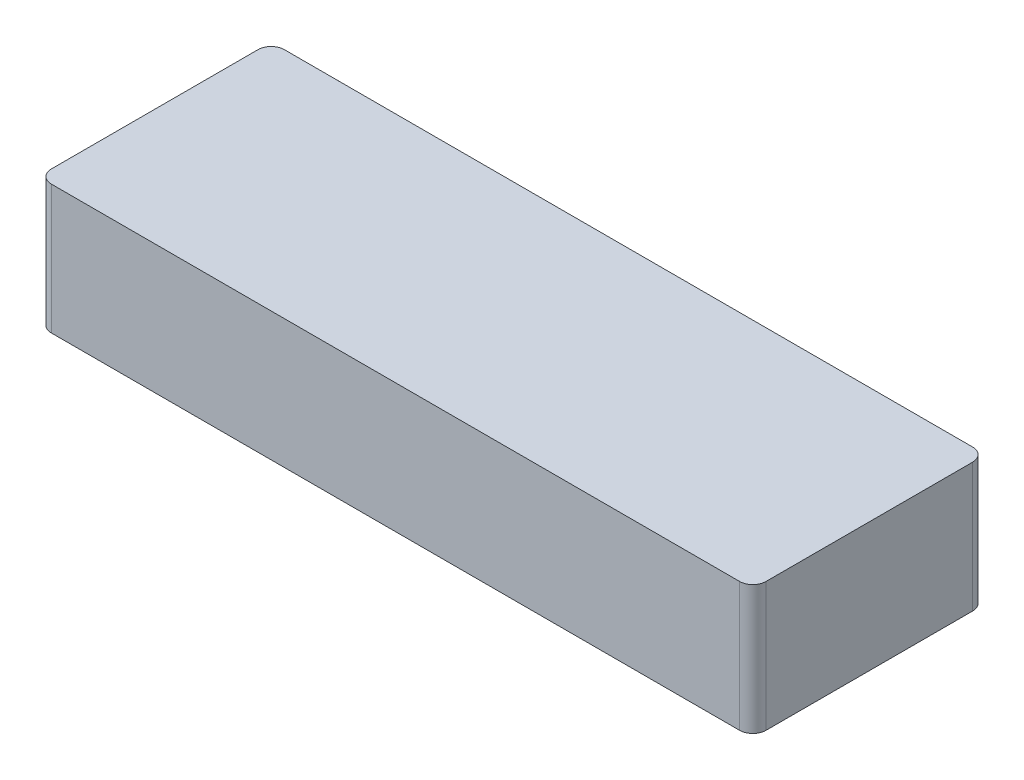
SolidWorks part; units mm, degrees
ref_plane "Front Plane" through (0, 0, 0) normal (0, 0, 1) x (1, 0, 0)
ref_plane "Top Plane" through (0, 0, 0) normal (0, 1, 0) x (1, 0, 0)
ref_plane "Right Plane" through (0, 0, 0) normal (1, 0, 0) x (0, 0, -1)
sketch "Sketch1" plane through (0, 0, 0) normal (0, 1, 0) x (1, 0, 0)
  line L1 (0, 0) -> (137.922, 0)
  line L2 (0, 0) -> (0, 44.958)
  line L3 (0, 44.958) -> (137.922, 44.958)
  line L4 (137.922, 0) -> (137.922, 44.958)
  dimension "D1" = 137.922
  dimension "D2" = 44.958
extrude "Boss-Extrude1" add sketch "Sketch1" along normal blind 24.892
fillet "Fillet1" radius 2.54 4 edges at (137.922, 12.446, -44.958) (137.922, 12.446, 0) (0, 12.446, -44.958) (0, 12.446, 0)
